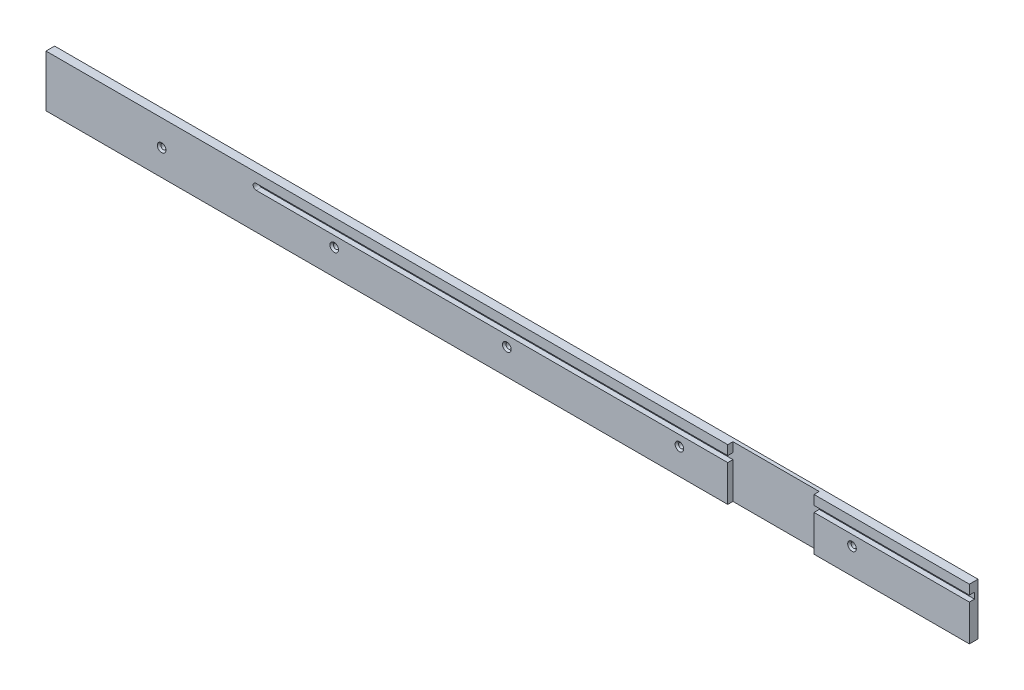
SolidWorks part; units mm, degrees
material "Холодостойкий пластик  -60 гр."
ref_plane "Спереди" through (0, 0, 0) normal (0, 0, 1) x (1, 0, 0)
ref_plane "Сверху" through (0, 0, 0) normal (0, 1, 0) x (1, 0, 0)
ref_plane "Справа" through (0, 0, 0) normal (1, 0, 0) x (0, 0, -1)
sketch "Эскиз1" plane through (0, 0, 0) normal (0, 0, 1) x (1, 0, 0)
  line L1 (-535, -30) -> (535, -30)
  line L2 (-535, -30) -> (-535, 30)
  line L3 (-535, 30) -> (535, 30)
  line L4 (535, -30) -> (535, 30)
  line L5 (0, 30) -> (0, -30) construction
  line L6 (-535, 0) -> (535, 0) construction
  point P0 (0, 0)
  dimension "D1" = 60
  dimension "D2" = 1070
extrude "Бобышка-Вытянуть1" add sketch "Эскиз1" along normal mid plane 10
sketch "Эскиз2" plane through (0, 0, 5) normal (0, 0, 1) x (1, 0, 0)
  line L1 (-291.5, 19) -> (255, 19)
  line L3 (-291.5, 12) -> (255, 12)
  line L4 (535, 19) -> (535, 12)
  line L5 (535, -30) -> (535, 30) construction
  line L6 (535, 30) -> (-535, 30) construction
  line L7 (-535, -30) -> (535, -30) construction
  line L8 (255, 30) -> (355, 30)
  line L9 (255, 30) -> (255, 19)
  line L10 (255, -30) -> (355, -30)
  line L11 (355, 30) -> (355, 19)
  line L12 (-535, 30) -> (-535, -30) construction
  line L13 (355, 19) -> (535, 19)
  line L14 (255, 12) -> (255, -30)
  line L15 (355, 12) -> (535, 12)
  line L16 (355, 12) -> (355, -30)
  arc A0 (-291.5, 12) -> (-291.5, 19) centre (-291.5, 15.5) cw
  dimension "D1" = 240
  dimension "D2" = 11
  dimension "D3" = 7
  dimension "D4" = 100
  dimension "D5" = 180
extrude "Вырез-Вытянуть1" cut sketch "Эскиз2" against normal blind 6
sketch "Эскиз3" plane through (0, 0, 5) normal (0, 0, 1) x (1, 0, 0)
  line L0 (355, -30) -> (535, -30) construction
  line L3 (399, 0) -> (535, 0) construction
  line L4 (535, -30) -> (535, 12) construction
  circle A0 centre (399, 0) radius 3
  dimension "D1" = 6
  dimension "D2" = 30
  dimension "D4" = 136
extrude "Вырез-Вытянуть2" cut sketch "Эскиз3" against normal through all
chamfer "Фаска1" distance 2 angle 45 1 edges at (402, 0, 5)
pattern_linear "Линейный массив1" count 5 spacing 200 along (-1, 0, 0) of "Вырез-Вытянуть2", "Фаска1"
mirror "Зеркальное отражение1" [suppressed]
